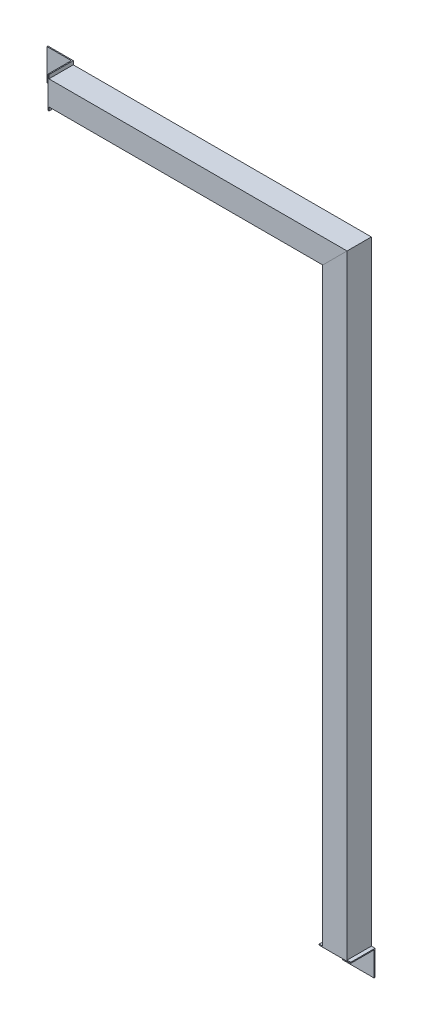
SolidWorks part; units mm, degrees
ref_plane "Front Plane" through (0, 0, 0) normal (0, 0, 1) x (1, 0, 0)
ref_plane "Top Plane" through (0, 0, 0) normal (0, 1, 0) x (1, 0, 0)
ref_plane "Right Plane" through (0, 0, 0) normal (1, 0, 0) x (0, 0, -1)
sketch "Sketch1" plane through (0, 0, 0) normal (0, 0, 1) x (1, 0, 0)
  line L0 (-615, 1265) -> (0, 1265)
  line L1 (0, 1265) -> (0, 0)
  dimension "D1" = 615
  dimension "D2" = 1265
sketch "Sketch2" plane through (0, 0, 0) normal (0, 1, 0) x (1, 0, 0)
  line L0 (-48, -23) -> (-48, 23)
  line L1 (-50, -25) -> (0, -25)
  line L2 (-50, -25) -> (-50, 25)
  line L3 (-50, 25) -> (0, 25)
  line L4 (0, -25) -> (0, 25)
  line L5 (-48, 23) -> (-2, 23)
  line L6 (-2, -23) -> (-2, 23)
  line L7 (-48, -23) -> (-2, -23)
  point P4 (0, 0)
  dimension "D1" = 50
  dimension "D2" = 2
sweep "Sweep1" add profiles "Sketch2" path "Sketch1"
sketch "Sketch3" plane through (0, 0, 25) normal (0, 0, 1) x (1, 0, 0)
  line L0 (-50, 0) -> (0, 0) construction
  line L1 (-57.5, 0) -> (7.5, 0)
  line L2 (-57.5, 0) -> (-57.5, -50)
  line L3 (-57.5, -50) -> (7.5, -50)
  line L4 (7.5, 0) -> (7.5, -50)
  point P4 (-25, 0)
  point P7 (-25, 0)
  dimension "D1" = 65
  dimension "D2" = 50
extrude "Boss-Extrude1" add sketch "Sketch3" against normal blind 2
sketch "Sketch4" plane through (0, 0, 25) normal (0, 0, 1) x (1, 0, 0)
  line L0 (-615, 1215) -> (-615, 1265) construction
  line L1 (-665, 1272.5) -> (-615, 1272.5)
  line L2 (-665, 1272.5) -> (-665, 1207.5)
  line L3 (-665, 1207.5) -> (-615, 1207.5)
  line L4 (-615, 1272.5) -> (-615, 1207.5)
  point P4 (-615, 1240)
  point P7 (-615, 1240)
  dimension "D1" = 65
  dimension "D2" = 50
extrude "Boss-Extrude2" add sketch "Sketch4" against normal blind 2
sketch "Sketch5" plane through (0, 0, 25) normal (0, 0, 1) x (1, 0, 0)
  line L0 (7.5, -50) -> (7.5, 0) construction
  line L1 (-615, 1272.5) -> (-613, 1272.5)
  line L2 (-615, 1272.5) -> (-615, 1207.5)
  line L3 (-615, 1207.5) -> (-613, 1207.5)
  line L4 (-613, 1272.5) -> (-613, 1207.5)
  line L5 (-57.5, 0) -> (7.5, 0)
  line L6 (-57.5, 0) -> (-57.5, 2)
  line L7 (-57.5, 2) -> (7.5, 2)
  line L8 (7.5, 0) -> (7.5, 2)
  line L9 (-665, 1207.5) -> (-615, 1207.5) construction
  point P10 (7.5, 1)
  dimension "D1" = 2
  dimension "D2" = 2
extrude "Boss-Extrude3" add sketch "Sketch5" against normal up to surface (50 mm away)
sketch "Sketch6" plane through (0, 0, 23) normal (0, 0, -1) x (-1, 0, 0)
  line L4 (57.5, 0) -> (-7.5, 0)
  line L5 (-7.5, 0) -> (-7.5, -50)
  line L6 (-7.5, -50) -> (57.5, -50)
  line L7 (57.5, -50) -> (57.5, 0)
  line L8 (57.5, 0) -> (-7.5, 0)
  line L9 (-7.5, 0) -> (-7.5, -50)
  line L10 (-7.5, -50) -> (57.5, -50)
  line L11 (57.5, -50) -> (57.5, 0)
  line L12 (615, 1272.5) -> (615, 1207.5)
  line L13 (615, 1207.5) -> (665, 1207.5)
  line L14 (665, 1207.5) -> (665, 1272.5)
  line L15 (665, 1272.5) -> (615, 1272.5)
  line L16 (615, 1272.5) -> (615, 1207.5)
  line L17 (615, 1207.5) -> (665, 1207.5)
  line L18 (665, 1207.5) -> (665, 1272.5)
  line L19 (665, 1272.5) -> (615, 1272.5)
  dimension "D1" = 0
  dimension "D2" = 0
extrude "Boss-Extrude4" add sketch "Sketch6" along normal up to surface (48 mm away)
sketch "Sketch7" plane through (0, 0, 25) normal (0, 0, 1) x (1, 0, 0)
  line L0 (-615, 1272.5) -> (-615, 1207.5)
  line L1 (-665, 1272.5) -> (-615, 1272.5)
  line L2 (-665, 1272.5) -> (-665, 1207.5)
  line L3 (-665, 1207.5) -> (-615, 1207.5)
  line L4 (-613, 1272.5) -> (-613, 1207.5) construction
  line L5 (-57.5, 2) -> (7.5, 2) construction
  line L6 (-57.5, 0) -> (-57.5, -50)
  line L7 (-57.5, -50) -> (7.5, -50)
  line L8 (7.5, 0) -> (7.5, -50)
  line L9 (-57.5, 0) -> (7.5, 0)
  dimension "D1" = 2
  dimension "D2" = 2
extrude "Cut-Extrude1" cut sketch "Sketch7" against normal offset from surface (48 mm away) 2
